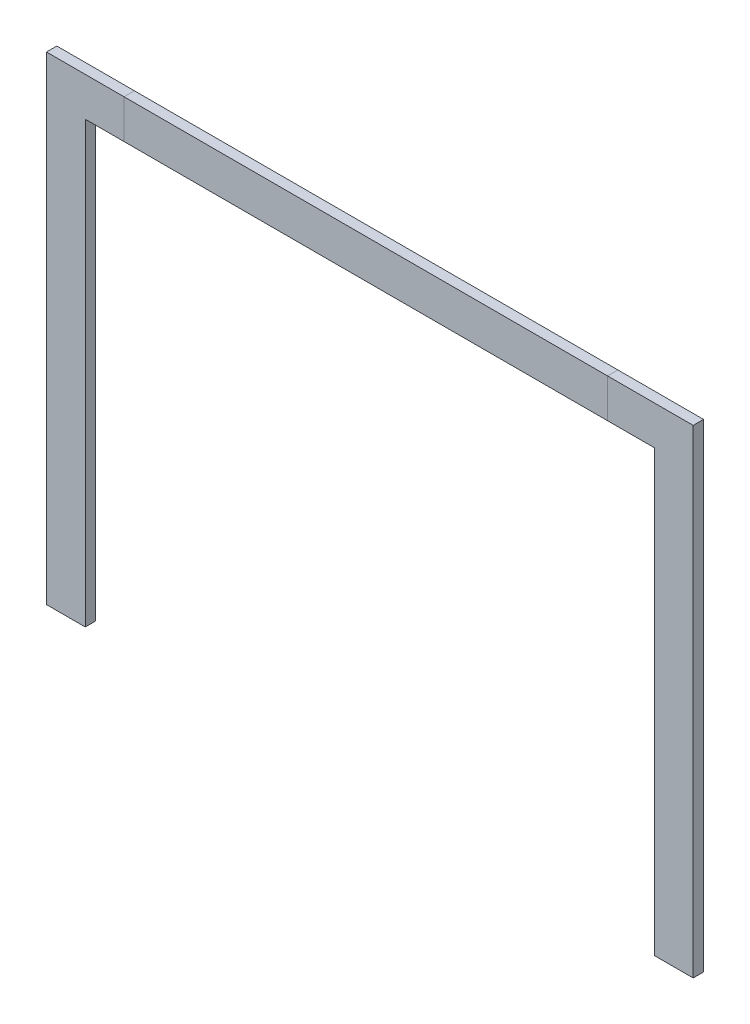
SolidWorks part; units mm, degrees
ref_plane "Front Plane" through (0, 0, 0) normal (0, 0, 1) x (1, 0, 0)
ref_plane "Top Plane" through (0, 0, 0) normal (0, 1, 0) x (1, 0, 0)
ref_plane "Right Plane" through (0, 0, 0) normal (1, 0, 0) x (0, 0, -1)
sketch "Sketch1" plane through (0, 0, 0) normal (0, 0, 1) x (1, 0, 0)
  line L1 (-125, -92.5) -> (125, -92.5)
  line L2 (-125, -92.5) -> (-125, 92.5)
  line L3 (-125, 92.5) -> (125, 92.5)
  line L4 (125, -92.5) -> (125, 92.5)
  line L5 (-125, -92.5) -> (125, 92.5) construction
  line L6 (-125, 92.5) -> (125, -92.5) construction
  point P1 (0, 0)
  dimension "D1" = 250
  dimension "D2" = 185
extrude "Boss-Extrude1" add sketch "Sketch1" along normal blind 4
sketch "Sketch2" plane through (0, 0, 0) normal (0, 0, -1) x (-1, 0, 0)
  line L0 (-91.8877, 60) -> (-91.8877, -92.5)
  line L1 (-91.8877, -92.5) -> (95, -92.5)
  line L2 (125, -92.5) -> (-125, -92.5) construction
  line L3 (-91.8877, 60) -> (95, 60)
  line L4 (95, -92.5) -> (95, 60)
extrude "Cut-Extrude2" cut sketch "Sketch2" against normal blind 10
sketch "Sketch3" plane through (0, 0, 4) normal (0, 0, 1) x (1, 0, 0)
  line L0 (91.8877, 60) -> (91.8877, -92.5) construction
  line L1 (-95, -92.5) -> (91.8877, -92.5)
  line L2 (-95, -92.5) -> (-95, -60)
  line L3 (-95, -60) -> (91.8877, -60)
  line L4 (91.8877, -92.5) -> (91.8877, -60)
  dimension "D1" = 32.5
extrude "Boss-Extrude2" add sketch "Sketch3" against normal blind 4
sketch "Sketch4" plane through (0, 0, 4) normal (0, 0, 1) x (1, 0, 0)
  line L0 (125, 92.5) -> (-125, 92.5) construction
  line L1 (-95, 60) -> (91.8877, 60)
  line L2 (-95, 60) -> (-95, 92.5)
  line L3 (-95, 92.5) -> (91.8877, 92.5)
  line L4 (91.8877, 60) -> (91.8877, 92.5)
extrude "Cut-Extrude3" cut sketch "Sketch4" against normal blind 4
sketch "Sketch5" plane through (0, 0, 4) normal (0, 0, 1) x (1, 0, 0)
  line L0 (-95, 92.5) -> (91.8877, 92.5)
  line L1 (-95, 62.5) -> (91.8877, 62.5)
  line L2 (-95, -60) -> (-95, 92.5) construction
  line L3 (91.8877, 92.5) -> (91.8877, -60) construction
  line L4 (91.8877, 62.5) -> (91.8877, 92.5)
  line L5 (-95, 62.5) -> (-95, 92.5)
  dimension "D1" = 30
extrude "Boss-Extrude3" add sketch "Sketch5" against normal blind 4 separate body
sketch "Sketch6" plane through (0, 0, 4) normal (0, 0, 1) x (1, 0, 0)
  line L1 (-125, -92.5) -> (125, -92.5) construction
  line L2 (-110, -92.5) -> (110, -92.5)
  line L3 (-110, -92.5) -> (-110, 77.5)
  line L4 (-110, 77.5) -> (110, 77.5)
  line L6 (110, -92.5) -> (110, 77.5)
  dimension "D2" = 15
  dimension "D3" = 15
extrude "Cut-Extrude5" cut sketch "Sketch6" against normal blind 4
sketch "Sketch7" plane through (0, 0, 4) normal (0, 0, 1) x (1, 0, 0)
  line L1 (-95, 62.5) -> (91.8877, 62.5)
  line L2 (-95, 62.5) -> (-95, 77.5)
  line L3 (-95, 77.5) -> (91.8877, 77.5)
  line L4 (91.8877, 62.5) -> (91.8877, 77.5)
extrude "Cut-Extrude6" cut sketch "Sketch7" against normal blind 4
